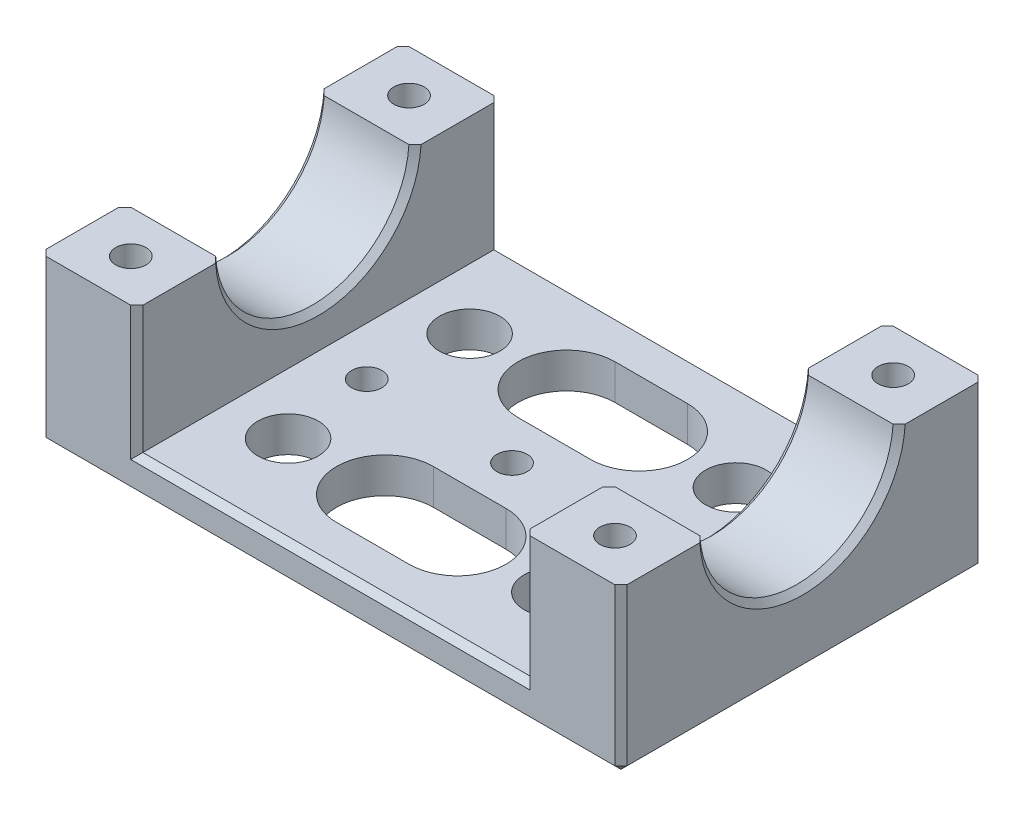
SolidWorks part; units mm, degrees
material "1060 Alloy"
ref_plane "Front Plane" through (0, 0, 0) normal (0, 0, 1) x (1, 0, 0)
ref_plane "Top Plane" through (0, 0, 0) normal (0, 1, 0) x (1, 0, 0)
ref_plane "Right Plane" through (0, 0, 0) normal (1, 0, 0) x (0, 0, -1)
sketch "Sketch2" plane through (0, 0, 0) normal (0, 1, 0) x (1, 0, 0)
  line L1 (16, -15) -> (-16, -15)
  line L2 (16, -15) -> (16, 15)
  line L3 (16, 15) -> (-16, 15)
  line L4 (-16, -15) -> (-16, 15)
  line L5 (16, -15) -> (-16, 15) construction
  line L6 (16, 15) -> (-16, -15) construction
  point P0 (0, 0)
  dimension "D1" = 30
  dimension "D2" = 32
extrude "Boss-Extrude1" add sketch "Sketch2" along normal blind 2.9227
sketch "Sketch3" plane through (0, 2.9227, 0) normal (0, 1, 0) x (1, 0, 0)
  line L0 (-16, 0) -> (16, 0) construction
  line L3 (-16, 15) -> (-16, -15) construction
  line L4 (-24, 15) -> (-16, 15)
  line L5 (-24, 15) -> (-24, -15)
  line L6 (-24, -15) -> (-16, -15)
  line L7 (-16, 15) -> (-16, -15)
  line L8 (-24, 15) -> (-16, -15) construction
  line L9 (-24, -15) -> (-16, 15) construction
  line L10 (24, -15) -> (16, -15)
  line L11 (24, -15) -> (24, 15)
  line L12 (24, 15) -> (16, 15)
  line L13 (16, -15) -> (16, 15)
  line L14 (24, -15) -> (16, 15) construction
  line L15 (24, 15) -> (16, -15) construction
  line L16 (16, -15) -> (16, 15) construction
  point P6 (-20, 0)
  point P12 (20, 0)
  dimension "D1" = 8
  dimension "D2" = 30
  dimension "D3" = 8
extrude "Boss-Extrude2" add sketch "Sketch3" along normal blind 25 and the other way up to surface (2.9227 mm away) other way up to face at (0, 0, 0)
sketch "Sketch4" plane through (24, 0, 0) normal (1, 0, 0) x (0, 0, -1)
  line L0 (-15, 13.9613) -> (15, 13.9613) construction
  line L1 (-15, 27.9227) -> (-15, 0) construction
  line L2 (15, 27.9227) -> (15, 0) construction
  circle A0 centre (0, 13.9613) radius 8
  dimension "D1" = 16
extrude "Cut-Extrude1" cut sketch "Sketch4" against normal through all both and the other way through all
hole_wizard "M3x0.5 Tapped Hole1" positions "Sketch5" profile "Sketch6" tap size "M3x0.5" standard "ANSI Metric" end condition through all
sketch "Sketch5" plane through (0, 2.9227, 0) normal (0, 1, 0) x (1, 0, 0)
  line L0 (-16, 0) -> (16, 0) construction
  line L1 (-16, -15) -> (-16, 15) construction
  line L2 (16, -15) -> (16, 15) construction
  point P8 (0, 0)
  point P11 (-12, 0)
  point P13 (12, 0)
  dimension "D1" = 12
  dimension "D2" = 12
sketch "Sketch6" plane through (12, 2.9227, 0) normal (1, 0, 0) x (0, 0, 1)
  line L0 (0, 0) -> (0, 2.9227)
  line L1 (0, 2.9227) -> (1.25, 2.9227)
  line L2 (1.25, 2.9227) -> (1.25, 0)
  line L5 (1.25, 0) -> (0, 0)
  line L11 (0, -6.35) -> (0, 107.95) construction
  dimension "Thru Tap Drill Dia." = 2.5
  dimension "Thru Tap Drill Depth" = 2.9227
cosmetic thread "Hole Thread2" parameters "D2"=3
cosmetic thread "Hole Thread3" parameters "D2"=3
cosmetic thread "Hole Thread8" parameters "D2"=3
sketch "Sketch7" plane through (0, 2.9227, 0) normal (0, 1, 0) x (1, 0, 0)
  line L0 (-16, 0) -> (16, 0) construction
  line L1 (-3, 7.5) -> (3, 7.5) construction
  line L2 (-3, 11.5) -> (3, 11.5)
  line L3 (-16, -15) -> (-16, 15) construction
  line L4 (16, -15) -> (16, 15) construction
  line L5 (-16, 7.5) -> (16, 7.5) construction
  line L6 (-16, 15) -> (-16, -15) construction
  line L7 (-16, -7.5) -> (16, -7.5) construction
  line L8 (-3, 3.5) -> (3, 3.5)
  line L9 (-3, -7.5) -> (3, -7.5) construction
  line L10 (-3, -3.5) -> (3, -3.5)
  line L11 (-3, -11.5) -> (3, -11.5)
  circle A0 centre (-11, 7.5) radius 2.5
  circle A1 centre (-11, -7.5) radius 2.5
  circle A8 centre (11, -7.5) radius 2.5
  circle A9 centre (11, 7.5) radius 2.5
  circle A10 centre (0, 7.5) radius 2.5 [skipped]
  circle A11 centre (0, -7.5) radius 2.5 [skipped]
  circle A12 centre (5.5, 7.5) radius 2.5 [skipped]
  circle A13 centre (-5.5, 7.5) radius 2.5 [skipped]
  circle A14 centre (-5.5, -7.5) radius 2.5 [skipped]
  circle A15 centre (5.5, -7.5) radius 2.5 [skipped]
  arc A16 (-3, 11.5) -> (-3, 3.5) centre (-3, 7.5) ccw
  arc A17 (3, 3.5) -> (3, 11.5) centre (3, 7.5) ccw
  arc A18 (-3, -3.5) -> (-3, -11.5) centre (-3, -7.5) ccw
  arc A19 (3, -11.5) -> (3, -3.5) centre (3, -7.5) ccw
  point P17 (0, 7.5)
  point P25 (0, -7.5)
  dimension "D3" = 5
  dimension "D5" = 5
  dimension "D8" = 8
  dimension "D1" = 7.5
  dimension "D2" = 7.5
  dimension "D4" = 5
  dimension "D7" = 5
  dimension "D9" = 8
  dimension "D10" = 8
  dimension "D11" = 8
  dimension "D6" = 5
extrude "Cut-Extrude2" cut sketch "Sketch7" against normal through all
sketch "Sketch8" plane through (24, 0, 0) normal (1, 0, 0) x (0, 0, -1)
  line L0 (-15, 0) -> (-15, 27.9227) construction
  line L1 (-15, 13.9613) -> (15, 13.9613)
  line L2 (-15, 13.9613) -> (-15, 32.9227)
  line L3 (-15, 32.9227) -> (15, 32.9227)
  line L4 (15, 13.9613) -> (15, 32.9227)
  line L5 (15, 0) -> (15, 27.9227) construction
  line L6 (-15, 27.9227) -> (15, 27.9227) construction
  dimension "D1" = 5
extrude "Cut-Extrude3" cut sketch "Sketch8" against normal through all
sketch "Sketch9" plane through (24, 0, 0) normal (1, 0, 0) x (0, 0, -1)
  line L0 (15, 0) -> (15, 13.9613) construction
  line L1 (-15, 13.9613) -> (15, 13.9613)
  line L2 (-15, 13.9613) -> (-15, 13.4613)
  line L3 (-15, 13.4613) -> (15, 13.4613)
  line L4 (15, 13.9613) -> (15, 13.4613)
  dimension "D1" = 0.5
extrude "Cut-Extrude4" cut sketch "Sketch9" against normal through all
hole_wizard "M3x0.5 Tapped Hole2" positions "Sketch10" profile "Sketch11" tap size "M3x0.5" standard "ANSI Metric" end condition through all
sketch "Sketch10" plane through (0, 13.4613, 0) normal (0, 1, 0) x (1, 0, 0)
  line L0 (-20, -15) -> (-20, -7.9844) construction
  line L1 (-24, -15) -> (-16, -15) construction
  line L2 (-24, -7.9844) -> (-16, -7.9844) construction
  line L4 (-20, 7.9844) -> (-20, 15) construction
  line L5 (-16, 7.9844) -> (-24, 7.9844) construction
  line L6 (-24, 15) -> (-16, 15) construction
  line L8 (20, -15) -> (20, -7.9844) construction
  line L9 (16, -15) -> (24, -15) construction
  line L10 (16, -7.9844) -> (24, -7.9844) construction
  line L12 (20, 7.9844) -> (20, 15) construction
  line L13 (24, 7.9844) -> (16, 7.9844) construction
  line L14 (16, 15) -> (24, 15) construction
  point P30 (20, -11.4922)
  point P32 (20, 11.4922)
  point P34 (-20, -11.4922)
  point P36 (-20, 11.4922)
sketch "Sketch11" plane through (-20, 13.4613, -11.4922) normal (1, 0, 0) x (0, 0, 1)
  line L0 (0, 0) -> (0, 13.4613)
  line L1 (0, 13.4613) -> (1.25, 13.4613)
  line L2 (1.25, 13.4613) -> (1.25, 0)
  line L5 (1.25, 0) -> (0, 0)
  line L11 (0, -6.35) -> (0, 107.95) construction
  dimension "Thru Tap Drill Dia." = 2.5
  dimension "Thru Tap Drill Depth" = 13.4613
cosmetic thread "Hole Thread4" parameters "D2"=3
cosmetic thread "Hole Thread5" parameters "D2"=3
cosmetic thread "Hole Thread6" parameters "D2"=3
cosmetic thread "Hole Thread7" parameters "D2"=3
chamfer "Chamfer1" distance 0.5 angle 45 18 edges at (24, 5.9613, 0) (16, 5.9613, 0) (16, 8.192, -15) (0, 2.9227, -15) (-16, 8.192, -15) (16, 8.192, 15) (-16, 8.192, 15) (0, 2.9227, 15) (-16, 5.9613, 0) (-24, 5.9613, 0) (-24, 6.7307, -15) (-24, 6.7307, 15) (-24, 0, 0) (0, 0, -15) (24, 6.7307, -15) (24, 0, 0) (0, 0, 15) (24, 6.7307, 15)
